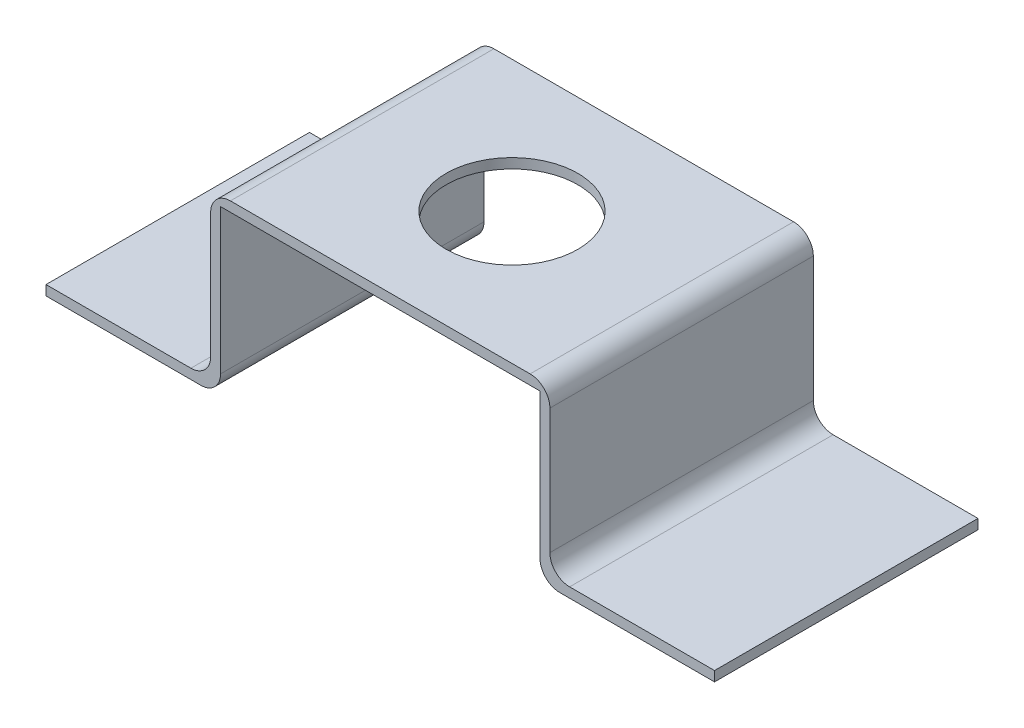
SolidWorks part; units mm, degrees
ref_plane "Front Plane" through (0, 0, 0) normal (0, 0, 1) x (1, 0, 0)
ref_plane "Top Plane" through (0, 0, 0) normal (0, 1, 0) x (1, 0, 0)
ref_plane "Right Plane" through (0, 0, 0) normal (1, 0, 0) x (0, 0, -1)
sketch "Sketch1" plane through (0, 0, 0) normal (0, 1, 0) x (1, 0, 0)
  line L0 (-12.5, -20) -> (12.5, -20)
  line L3 (-12.5, -20) -> (-12.5, 20)
  line L4 (-12.5, 20) -> (12.5, 20)
  line L5 (12.5, 20) -> (12.5, -20)
extrude "Boss-Extrude1" add sketch "Sketch1" along normal blind 1.5
ref_plane "Plane1" through (12.5, 0, 0) normal (1, 0, 0) x (0, 0, -1)
sketch "Sketch5" plane through (12.5, 0, 0) normal (1, 0, 0) x (0, 0, -1)
  line L0 (-20, 0) -> (-20, 25)
  line L1 (-20, 25) -> (20, 25)
  line L2 (20, 25) -> (20, 0)
  line L3 (20, 1.5) -> (20, 0) construction
  line L4 (-20, 0) -> (20, 0) construction
  line L5 (20, 0) -> (-20, 0)
extrude "Boss-Extrude3" add sketch "Sketch5" along normal blind 1.5
sketch "Sketch6" plane through (0, 25, 0) normal (0, 1, 0) x (1, 0, 0)
  line L0 (12.5, 20) -> (62.5, 20)
  line L1 (12.5, -13.75) -> (12.5, 13.75) construction
  line L2 (12.5, 20) -> (-12.5, 20) construction
  line L3 (62.5, 20) -> (62.5, -20)
  line L4 (62.5, -20) -> (12.5, -20)
  line L5 (12.5, 20) -> (12.5, -20)
extrude "Boss-Extrude4" add sketch "Sketch6" along normal blind 1.5
sketch "Sketch7" plane through (62.5, 0, 0) normal (1, 0, 0) x (0, 0, -1)
  line L0 (-20, 26.5) -> (-20, 0)
  line L1 (-20, 0) -> (20, 0)
  line L2 (20, 0) -> (20, 26.5)
  line L3 (20, 26.5) -> (-20, 26.5)
extrude "Boss-Extrude5" add sketch "Sketch7" along normal blind 1.5
sketch "Sketch9" plane through (0, 0, 0) normal (0, 1, 0) x (1, 0, 0)
  line L0 (64, 20) -> (89, 20)
  line L1 (89, 20) -> (89, -20)
  line L2 (89, -20) -> (64, -20)
  line L3 (64, -20) -> (64, 20)
extrude "Boss-Extrude6" add sketch "Sketch9" along normal blind 1.5
fillet "Fillet2" radius 3 4 edges at (64, 26.5, 0) (62.5, 0, 0) (14, 0, 0) (12.5, 26.5, 0)
sketch "Sketch10" plane through (0, 26.5, 0) normal (0, 1, 0) x (1, 0, 0)
  circle A1 centre (38.25, 0) radius 10
extrude "Cut-Extrude1" cut sketch "Sketch10" against normal blind 1.5
fillet "Fillet3" radius 3 2 edges at (64, 1.5, 0) (12.5, 1.5, 0)
